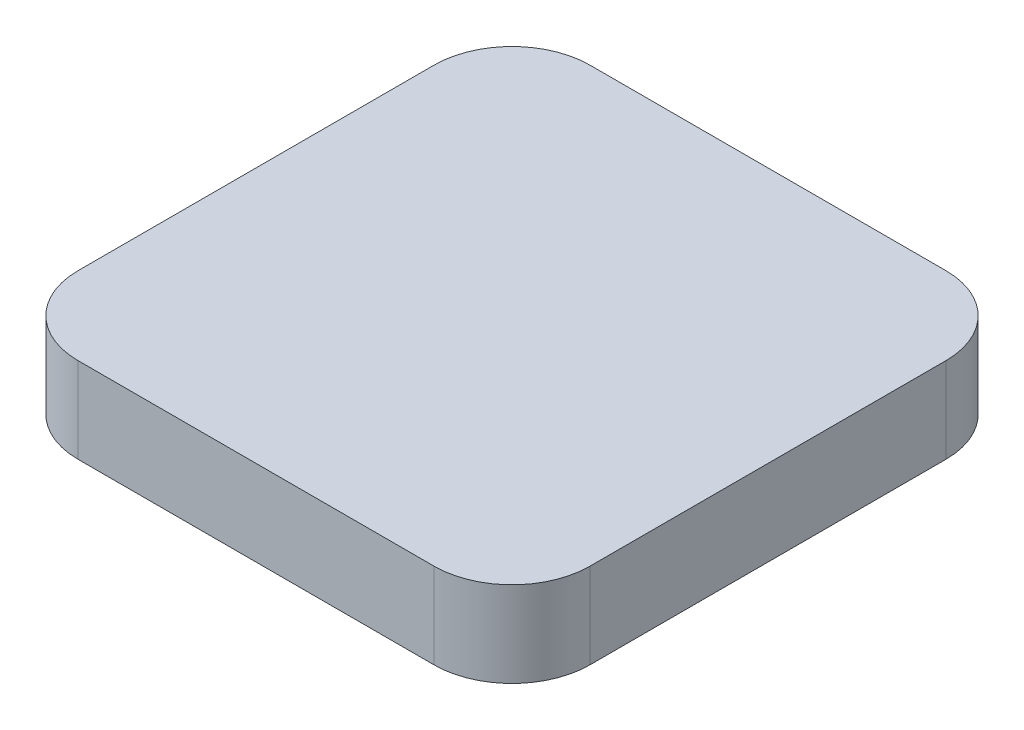
SolidWorks part; units mm, degrees
ref_plane "Front Plane" through (0, 0, 0) normal (0, 0, 1) x (1, 0, 0)
ref_plane "Top Plane" through (0, 0, 0) normal (0, 1, 0) x (1, 0, 0)
ref_plane "Right Plane" through (0, 0, 0) normal (1, 0, 0) x (0, 0, -1)
sketch "Sketch1" plane through (0, 0, 0) normal (0, 1, 0) x (1, 0, 0)
  line L1 (-8.6995, -12.5095) -> (8.6995, -12.5095)
  line L2 (-12.5095, -8.6995) -> (-12.5095, 8.6995)
  line L3 (-8.6995, 12.5095) -> (8.6995, 12.5095)
  line L4 (12.5095, -8.6995) -> (12.5095, 8.6995)
  line L5 (-12.5095, -12.5095) -> (12.5095, 12.5095) construction
  line L6 (-12.5095, 12.5095) -> (12.5095, -12.5095) construction
  arc A0 (-8.6995, -12.5095) -> (-12.5095, -8.6995) centre (-8.6995, -8.6995) cw
  arc A1 (8.6995, -12.5095) -> (12.5095, -8.6995) centre (8.6995, -8.6995) ccw
  arc A2 (8.6995, 12.5095) -> (12.5095, 8.6995) centre (8.6995, 8.6995) cw
  arc A3 (-12.5095, 8.6995) -> (-8.6995, 12.5095) centre (-8.6995, 8.6995) cw
  point P0 (0, 0)
  dimension "D3" = 3.81
  dimension "D1" = 25.019
  dimension "D2" = 25.019
extrude "Boss-Extrude1" add sketch "Sketch1" along normal blind 4.1783
